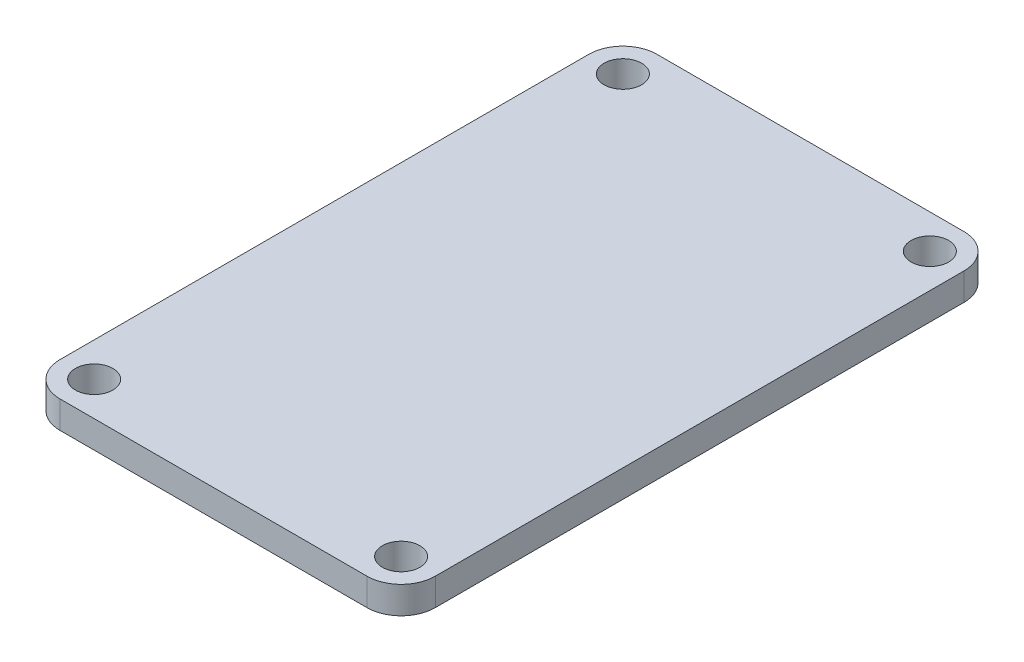
SolidWorks part; units mm, degrees
ref_plane "前视基准面" through (0, 0, 0) normal (0, 0, 1) x (1, 0, 0)
ref_plane "上视基准面" through (0, 0, 0) normal (0, 1, 0) x (1, 0, 0)
ref_plane "右视基准面" through (0, 0, 0) normal (1, 0, 0) x (0, 0, -1)
sketch "草图1" plane through (0, 0, 0) normal (0, 1, 0) x (1, 0, 0)
  line L1 (-11, 17.5) -> (11, 17.5)
  line L2 (-11, 17.5) -> (-11, -17.5)
  line L3 (-11, -17.5) -> (11, -17.5)
  line L4 (11, 17.5) -> (11, -17.5)
  line L5 (-11, 17.5) -> (11, -17.5) construction
  line L6 (-11, -17.5) -> (11, 17.5) construction
  point P0 (0, 0)
  dimension "D1" = 22
  dimension "D2" = 35
extrude "凸台-拉伸1" add sketch "草图1" along normal blind 1.6
sketch "草图2" plane through (0, 1.6, 0) normal (0, 1, 0) x (1, 0, 0)
  line L0 (0, 7.2243) -> (0, -3.7287) construction
  line L1 (2.7499, 0) -> (-2.7033, 0) construction
  line L2 (11, 17.5) -> (-11, 17.5) construction
  line L3 (-11, 17.5) -> (-11, -17.5) construction
  circle A0 centre (-9, 15.5) radius 1.1
  circle A1 centre (9, 15.5) radius 1.1
  circle A2 centre (9, -15.5) radius 1.1
  circle A3 centre (-9, -15.5) radius 1.1
  dimension "D1" = 2.2
  dimension "D2" = 2
  dimension "D3" = 2
extrude "切除-拉伸1" cut sketch "草图2" against normal through all
fillet "圆角2" radius 2 4 edges at (11, 0.8, -17.5) (11, 0.8, 17.5) (-11, 0.8, 17.5) (-11, 0.8, -17.5)
